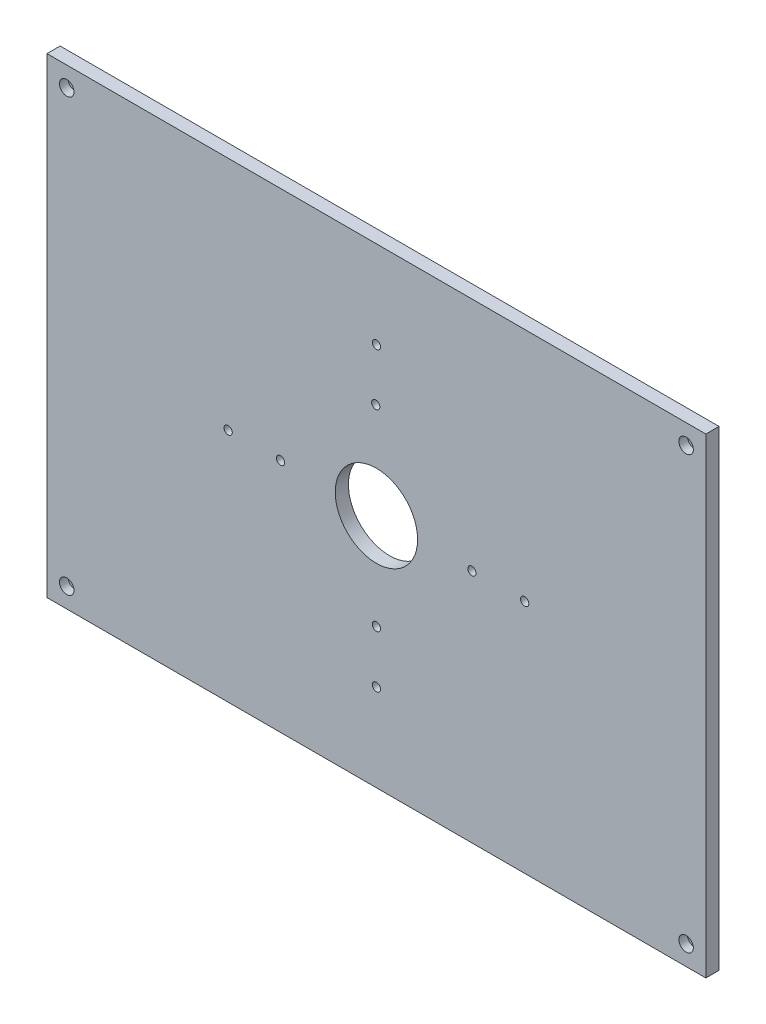
SolidWorks part; units mm, degrees
ref_plane "Front Plane" through (0, 0, 0) normal (0, 0, 1) x (1, 0, 0)
ref_plane "Top Plane" through (0, 0, 0) normal (0, 1, 0) x (1, 0, 0)
ref_plane "Right Plane" through (0, 0, 0) normal (1, 0, 0) x (0, 0, -1)
sketch "Sketch1" plane through (0, 0, 0) normal (0, 0, 1) x (1, 0, 0)
  line L1 (0, 0) -> (254, 0)
  line L2 (0, 0) -> (0, 181.61)
  line L3 (0, 181.61) -> (254, 181.61)
  line L4 (254, 0) -> (254, 181.61)
  dimension "D1" = 181.61
  dimension "D2" = 254
extrude "Boss-Extrude1" add sketch "Sketch1" along normal blind 5.08
sketch "Sketch2" plane through (0, 0, 5.08) normal (0, 0, 1) x (1, 0, 0)
  line L0 (254, 181.61) -> (0, 181.61) construction
  line L1 (254, 0) -> (254, 181.61) construction
  circle A0 centre (127, 90.805) radius 15.875
  dimension "D1" = 31.75
  dimension "D2" = 90.805
  dimension "D3" = 127
extrude "Cut-Extrude1" cut sketch "Sketch2" against normal blind 5.08
sketch "Sketch3" plane through (0, 0, 5.08) normal (0, 0, 1) x (1, 0, 0)
  line L0 (254, 181.61) -> (0, 181.61) construction
  line L1 (0, 181.61) -> (0, 0) construction
  line L2 (254, 0) -> (254, 181.61) construction
  line L3 (0, 0) -> (254, 0) construction
  circle A0 centre (7.62, 173.99) radius 1.5875
  circle A1 centre (246.38, 173.99) radius 1.5875
  circle A2 centre (7.62, 7.62) radius 1.5875
  circle A3 centre (246.38, 7.62) radius 1.5875
  dimension "D1" = 3.175
  dimension "D2" = 3.175
  dimension "D3" = 3.175
  dimension "D4" = 3.175
  dimension "D5" = 7.62
  dimension "D6" = 7.62
  dimension "D7" = 7.62
  dimension "D8" = 7.62
  dimension "D9" = 7.62
  dimension "D10" = 7.62
  dimension "D11" = 7.62
  dimension "D12" = 7.62
extrude "Cut-Extrude3" cut sketch "Sketch3" against normal blind 7.62
sketch "Sketch4" plane through (0, 0, 5.08) normal (0, 0, 1) x (1, 0, 0)
  line L0 (127, 181.61) -> (127, 156.0291) construction
  line L1 (10.287, 173.99) -> (8.9535, 176.2997)
  line L2 (8.9535, 176.2997) -> (6.2865, 176.2997)
  line L3 (6.2865, 176.2997) -> (4.953, 173.99)
  line L4 (4.953, 173.99) -> (6.2865, 171.6803)
  line L5 (6.2865, 171.6803) -> (8.9535, 171.6803)
  line L6 (8.9535, 171.6803) -> (10.287, 173.99)
  line L7 (254, 181.61) -> (0, 181.61) construction
  line L8 (0, 90.805) -> (24.1764, 90.805) construction
  line L9 (0, 181.61) -> (0, 0) construction
  line L10 (245.0465, 171.6803) -> (243.713, 173.99)
  line L11 (247.7135, 171.6803) -> (245.0465, 171.6803)
  line L12 (249.047, 173.99) -> (247.7135, 171.6803)
  line L13 (247.7135, 176.2997) -> (249.047, 173.99)
  line L14 (245.0465, 176.2997) -> (247.7135, 176.2997)
  line L15 (243.713, 173.99) -> (245.0465, 176.2997)
  line L16 (6.2865, 9.9297) -> (8.9535, 9.9297)
  line L17 (8.9535, 9.9297) -> (10.287, 7.62)
  line L18 (4.953, 7.62) -> (6.2865, 9.9297)
  line L19 (6.2865, 5.3103) -> (4.953, 7.62)
  line L20 (8.9535, 5.3103) -> (6.2865, 5.3103)
  line L21 (10.287, 7.62) -> (8.9535, 5.3103)
  line L22 (245.0465, 5.3103) -> (247.7135, 5.3103)
  line L23 (247.7135, 5.3103) -> (249.047, 7.62)
  line L24 (249.047, 7.62) -> (247.7135, 9.9297)
  line L25 (247.7135, 9.9297) -> (245.0465, 9.9297)
  line L26 (243.713, 7.62) -> (245.0465, 5.3103)
  line L27 (245.0465, 9.9297) -> (243.713, 7.62)
  circle A0 centre (7.62, 173.99) radius 2.3097 construction
  circle A1 centre (246.38, 173.99) radius 2.3097 construction
  circle A2 centre (7.62, 7.62) radius 2.3097 construction
  circle A3 centre (246.38, 7.62) radius 2.3097 construction
  dimension "D1" = 5.334
extrude "Cut-Extrude4" [suppressed] cut sketch "Sketch4" against normal blind 2.286
sketch "Sketch5" plane through (0, 0, 5.08) normal (0, 0, 1) x (1, 0, 0)
  circle A0 centre (246.38, 173.99) radius 2.794
  circle A1 centre (246.38, 7.62) radius 2.794
  circle A2 centre (7.62, 173.99) radius 2.794
  circle A3 centre (7.62, 7.62) radius 2.794
  dimension "D1" = 5.588
  dimension "D2" = 5.588
  dimension "D3" = 5.588
  dimension "D4" = 5.588
extrude "Cut-Extrude5" cut sketch "Sketch5" against normal blind 3.302
sketch "Sketch6" plane through (0, 0, 5.08) normal (0, 0, 1) x (1, 0, 0)
  line L0 (0, 181.61) -> (0, 0) construction
  circle A1 centre (127, 147.955) radius 1.5875
  circle A2 centre (184.15, 90.805) radius 1.5875
  circle A3 centre (127, 33.655) radius 1.5875
  circle A4 centre (69.85, 90.805) radius 1.5875
  circle A6 centre (163.83, 90.805) radius 1.5875
  circle A7 centre (127, 53.848) radius 1.5875
  circle A8 centre (90.043, 90.805) radius 1.5875
  circle A9 centre (126.746, 127.7611) radius 1.5875
  circle A10 centre (127, 90.805) radius 15.875 construction
  dimension "D1" = 57.15
  dimension "D2" = 3.175
  dimension "D3" = 3.175
  dimension "D4" = 3.175
  dimension "D5" = 3.175
  dimension "D6" = 3.175
  dimension "D7" = 3.175
  dimension "D8" = 3.175
  dimension "D9" = 3.175
  dimension "D10" = 57.15
  dimension "D11" = 57.15
  dimension "D12" = 57.15
  dimension "D13" = 36.83
  dimension "D14" = 36.957
  dimension "D15" = 36.957
  dimension "D16" = 36.957
  dimension "D17" = 126.746
extrude "Cut-Extrude6" cut sketch "Sketch6" against normal blind 5.08
